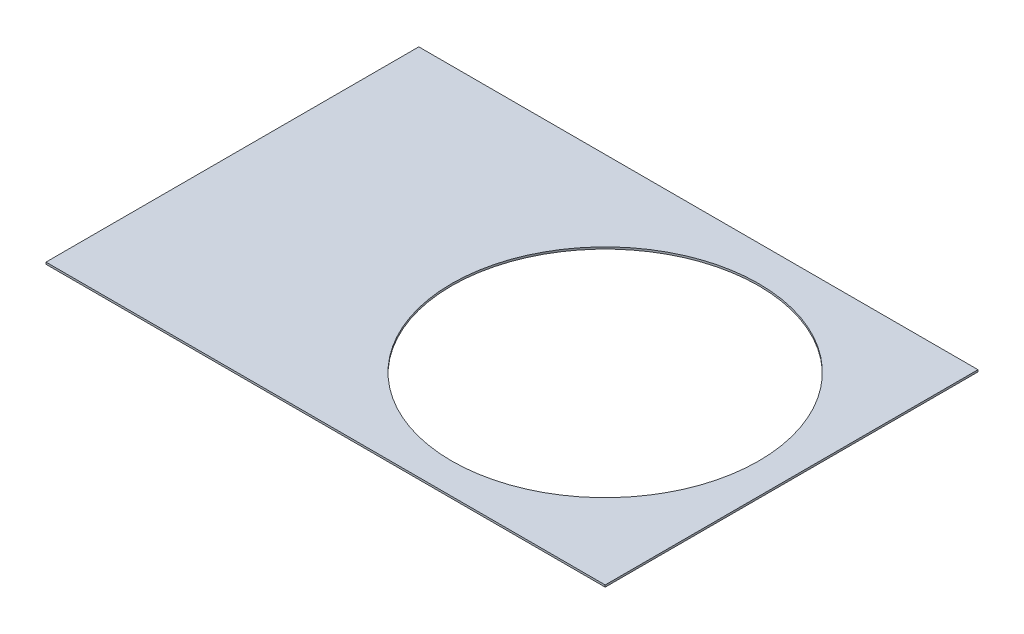
SolidWorks part; units mm, degrees
material "AISI 1035 Steel (SS)"
ref_plane "Frontal Plane" through (0, 0, 0) normal (0, 0, 1) x (1, 0, 0)
ref_plane "Horizontal Plane" through (0, 0, 0) normal (0, 1, 0) x (1, 0, 0)
ref_plane "Profile Plane" through (0, 0, 0) normal (1, 0, 0) x (0, 0, -1)
sketch "Sketch1" plane through (0, 0, 0) normal (0, 1, 0) x (1, 0, 0)
  line L1 (-457.2, -304.8) -> (457.2, -304.8)
  line L2 (-457.2, -304.8) -> (-457.2, 304.8)
  line L3 (-457.2, 304.8) -> (457.2, 304.8)
  line L4 (457.2, -304.8) -> (457.2, 304.8)
  circle A0 centre (156.0492, -3.6492) radius 251.1508
  point P0 (0, 0)
  point P10 (-457.2, 0)
  point P11 (0, 304.8)
  dimension "D3" = 502.3016
  dimension "D1" = 914.4
  dimension "D2" = 609.6
  dimension "D4" = 301.1508
  dimension "D5" = 301.1508
extrude "Boss-Extrude1" add sketch "Sketch1" along normal blind 3.175
equation "\"D2@Sketch1\" = \"BottomPlateZ\""
equation "\"D1@Sketch1\"=\"BottomPlateX\""
equation "\"BottomPlateX\"= 3ft"
equation "\"ArmPlateX\"= 18in"
equation "\"WallThickness\"= 0.5cm"
equation "\"Box-X\"= 40cm"
equation "\"Box-Z\"= 20cm"
equation "\"Box-Y\"= 30cm"
equation "\"ArmPlateThickness\"= .125in"
equation "\"DCMotor1D\"= 65mm"
equation "\"DCMotor2X\"= 68mm"
equation "\"DCMotor2D\"= 65mm"
equation "\"DCMotor2L\"= 208mm"
equation "\"DCMotor2ShaftL\"= 39mm"
equation "\"D3@Sketch1\"=\"BottomPlateHoleD\""
equation "\"DCMotor1ShaftL\"= 30mm"
equation "\"BenchDepth\"= 5cm"
equation "\"BenchH\"= 10cm"
equation "\"BenchL\"= 15cm"
equation "\"DCMotor1L\"= 215mm"
equation "\"ActuatorPinD\"= 6.35mm"
equation "\"ActuatorPinL\"= 15cm"
equation "\"DCMotor2ShaftD\"= 15mm"
equation "\"PillowBlockW\"= 5cm"
equation "\"PillowBlockCenterH\"= \"DCMotor2X\"/2"
equation "\"EncoderRadius\"= 19mm"
equation "\"EncoderShaftL\"= 15mm"
equation "\"EncoderL\"= 33mm"
equation "\"EncoderHousingThickness\"= 7.5mm"
equation "\"ArmPlateDepth\"= 7.1875in"
equation "\"TurntableID\"= 70mm"
equation "\"TurntableOD\"= 120mm"
equation "\"D4@Sketch1\"=\"BottomPlateHoleD\"*.5 +5cm"
equation "\"BottomPlateHoleD\"=((\"ArmPlateX\")^2+(\"ArmPlateDepth\")^2)^.5+ 10mm"
equation "\"TurntableInnerHoleRadius\"= \"TurntableID\"*.5 + \"TurntableInner2*t\"*.5"
equation "\"BottomPlateZ\"= 2ft"
equation "\"D5@Sketch1\"=\"BottomPlateHoleD\"*.5 + 5cm"
equation "\"TurntableInner2*t\" = (\"TurntableOD\"-\"TurntableID\")*.25 - 1mm"
equation "\"TurntableOuterHoleRadius\" = \"TurntableOD\"*.5 - ((\"TurntableOD\"-\"TurntableID\")*.25-.5mm)*.5"
equation "\"4040Height\"= 30cm"
equation "\"D1\" = \"DCMotor1ShaftL\" + \"DCMotor1L\""
equation "\"D1@Sketch2\"=\"WallThickness\""
